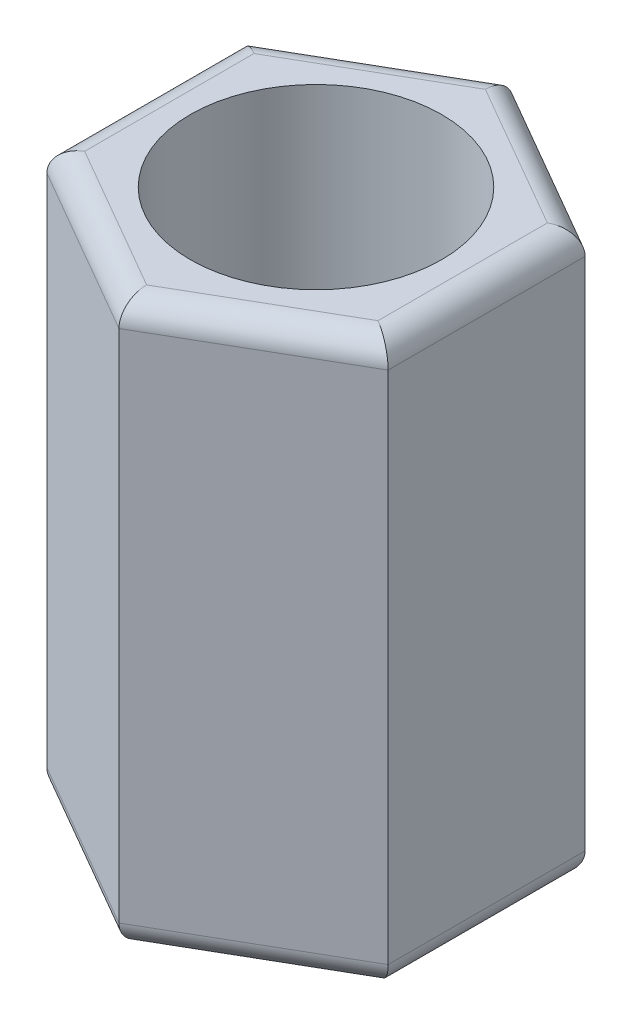
SolidWorks part; units mm, degrees
material "Brass"
ref_plane "Front Plane" through (0, 0, 0) normal (0, 0, 1) x (1, 0, 0)
ref_plane "Top Plane" through (0, 0, 0) normal (0, 1, 0) x (1, 0, 0)
ref_plane "Right Plane" through (0, 0, 0) normal (1, 0, 0) x (0, 0, -1)
sketch "Sketch1" plane through (0, 0, 0) normal (0, 1, 0) x (1, 0, 0)
  line L1 (1.425, 0.8227) -> (0, 1.6454)
  line L2 (0, 1.6454) -> (-1.425, 0.8227)
  line L3 (-1.425, 0.8227) -> (-1.425, -0.8227)
  line L4 (-1.425, -0.8227) -> (0, -1.6454)
  line L5 (0, -1.6454) -> (1.425, -0.8227)
  line L6 (1.425, -0.8227) -> (1.425, 0.8227)
  circle A0 centre (0, 0) radius 1.425 construction
  circle A1 centre (0, 0) radius 1.05
  dimension "D2" = 2.1
  dimension "D1" = 2.85
extrude "Boss-Extrude1" add sketch "Sketch1" along normal blind 4.7
fillet "Fillet1" radius 0.2 12 edges at (0.7125, 0, -1.2341) (1.425, 0, 0) (0.7125, 0, 1.2341) (-0.7125, 0, 1.2341) (-0.7125, 0, -1.2341) (-1.425, 0, 0) (-1.425, 4.7, 0) (-0.7125, 4.7, -1.2341) (0.7125, 4.7, -1.2341) (1.425, 4.7, 0) (0.7125, 4.7, 1.2341) (-0.7125, 4.7, 1.2341)
